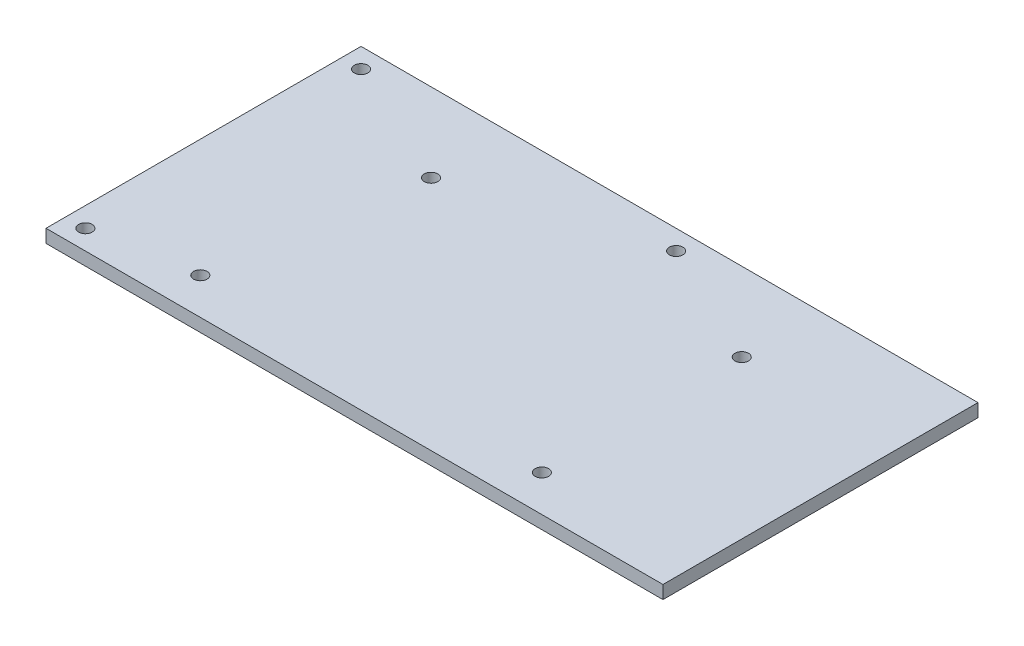
SolidWorks part; units mm, degrees
material "ABS"
ref_plane "Front Plane" through (0, 0, 0) normal (0, 0, 1) x (1, 0, 0)
ref_plane "Top Plane" through (0, 0, 0) normal (0, 1, 0) x (1, 0, 0)
ref_plane "Right Plane" through (0, 0, 0) normal (1, 0, 0) x (0, 0, -1)
sketch "Base Sketch" plane through (0, 0, 0) normal (0, 1, 0) x (1, 0, 0)
  line L1 (-74.6125, -38.1) -> (74.6125, -38.1)
  line L2 (-74.6125, -38.1) -> (-74.6125, 38.1)
  line L3 (-74.6125, 38.1) -> (74.6125, 38.1)
  line L4 (74.6125, -38.1) -> (74.6125, 38.1)
  line L5 (-74.6125, -38.1) -> (74.6125, 38.1) construction
  line L6 (-74.6125, 38.1) -> (74.6125, -38.1) construction
  point P0 (0, 0)
  dimension "D1" = 149.225
  dimension "D2" = 76.2
extrude "Boss-Extrude1" add sketch "Base Sketch" along normal blind 3.175
sketch "4-40 Hole Pattern Sketch (Guide Rail)" plane through (0, 3.175, 0) normal (0, 1, 0) x (1, 0, 0)
  line L0 (74.6125, 38.1) -> (-74.6125, 38.1) construction
  line L1 (-74.6125, 38.1) -> (-74.6125, -38.1) construction
  line L2 (-74.6125, -38.1) -> (74.6125, -38.1) construction
  circle A0 centre (-69.85, 33.3375) radius 1.6319
  circle A1 centre (6.35, 33.3375) radius 1.6319
  circle A2 centre (-69.85, -33.3375) radius 1.6319
  point P0 (-69.85, 33.3375)
  point P5 (6.35, 33.3375)
  point P6 (-69.85, -33.3375)
  dimension "D7" = 3.2639
  dimension "D8" = 3.2639
  dimension "D9" = 3.2639
  dimension "D1" = 4.7625
  dimension "D2" = 4.7625
  dimension "D3" = 4.7625
  dimension "D4" = 80.9625
  dimension "D5" = 4.7625
  dimension "D6" = 4.7625
sketch "4-40 Hole Pattern Sketch (Arduino Holes)" plane through (0, 3.175, 0) normal (0, 1, 0) x (1, 0, 0)
  line L0 (74.6125, -38.1) -> (74.6125, 38.1) construction
  line L1 (74.6125, 38.1) -> (-74.6125, 38.1) construction
  circle A0 centre (-38.6207, 19.05) radius 1.6319
  circle A1 centre (-46.1137, -29.2862) radius 1.6319
  circle A2 centre (36.5125, -29.2862) radius 1.6319
  circle A3 centre (36.5125, 19.05) radius 1.6319
  point P0 (36.5125, 19.05)
  point P5 (36.5125, -29.2862)
  point P6 (-38.6207, 19.05)
  point P7 (-46.1137, -29.2862)
  dimension "D9" = 3.2639
  dimension "D10" = 3.2639
  dimension "D11" = 3.2639
  dimension "D12" = 3.2639
  dimension "D1" = 38.1
  dimension "D2" = 19.05
  dimension "D3" = 38.1
  dimension "D4" = 48.3362
  dimension "D5" = 75.1332
  dimension "D6" = 19.05
  dimension "D7" = 48.3362
  dimension "D8" = 82.6262
extrude "Cut-Extrude1" cut sketch "4-40 Hole Pattern Sketch (Guide Rail)" against normal up to next
extrude "Cut-Extrude2" cut sketch "4-40 Hole Pattern Sketch (Arduino Holes)" against normal up to next
